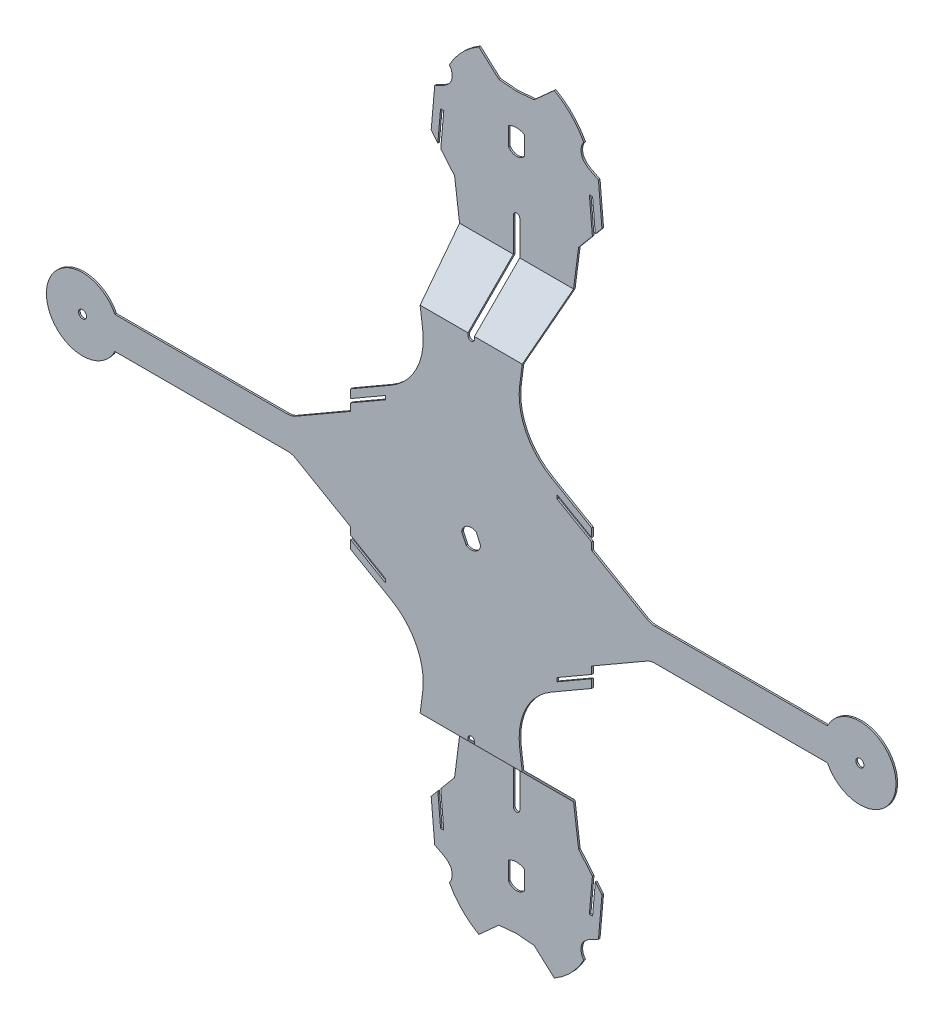
SolidWorks part; units mm, degrees
ref_plane "Alzado" through (0, 0, 0) normal (0, 0, 1) x (1, 0, 0)
ref_plane "Planta" through (0, 0, 0) normal (0, 1, 0) x (1, 0, 0)
ref_plane "Vista lateral" through (0, 0, 0) normal (1, 0, 0) x (0, 0, -1)
sketch "Croquis1" plane through (0, 0, 0) normal (1, 0, 0) x (0, 0, -1)
  line L2 (-31.6304, 0) -> (31.6304, 0) construction
  line L13 (17.5, 0) -> (17.5, 110)
  line L14 (17.5, 110) -> (45.7489, 138.2489)
  line L15 (45.7489, 138.2489) -> (45.7489, 248)
  line L16 (18.5, 0) -> (18.5, 109.5858)
  line L17 (18.5, 109.5858) -> (46.7489, 137.8347)
  line L18 (46.7489, 137.8347) -> (46.7489, 248)
  line L19 (45.7489, 248) -> (46.7489, 248)
  line L20 (45.7489, -248) -> (46.7489, -248)
  line L21 (46.7489, -137.8347) -> (46.7489, -248)
  line L22 (18.5, -109.5858) -> (46.7489, -137.8347)
  line L23 (18.5, 0) -> (18.5, -109.5858)
  line L24 (45.7489, -138.2489) -> (45.7489, -248)
  line L25 (17.5, -110) -> (45.7489, -138.2489)
  line L26 (17.5, 0) -> (17.5, -110)
  point P3 (0, 0)
  dimension "D1" = 17.5
  dimension "D2" = 110
  dimension "D3" = 45
  dimension "D4" = 39.95
  dimension "D5" = 496
  dimension "D6" = 1
extrude "Saliente-Extruir1" add sketch "Croquis1" along normal mid plane 542
sketch "Croquis5" plane through (0, 0, 0) normal (0, 0, 1) x (1, 0, 0)
  line L0 (-923.9507, 561.734) -> (-241.388, 573.6482) construction
sketch "Croquis2" plane through (0, 0, 0) normal (0, 0, 1) x (1, 0, 0)
  line L1 (0, 277.0309) -> (0, -277.0309) construction
  line L9 (-300.4496, 0) -> (300.4496, 0) construction
  line L10 (0, 108.5) -> (0, 159.5) construction
  line L11 (-2, 108.5) -> (-2, 159.5)
  line L12 (2, 108.5) -> (2, 159.5)
  line L13 (-30, 152) -> (-47.205, 172.5041) construction
  line L14 (-53.1684, 179.6111) -> (-50.9701, 204.7381)
  line L15 (-23.5, 239.2795) -> (-11, 228.0419)
  line L34 (-11, 228.0419) -> (0, 227.0795)
  line L35 (-49.0231, 174.6708) -> (-47.3316, 194.0041)
  line L36 (-47.3316, 194.0041) -> (-45.324, 194.0041)
  line L37 (-45.324, 194.0041) -> (-47.205, 172.5041)
  line L38 (-49.0231, 174.6708) -> (-53.1684, 179.6111)
  line L45 (-38.6025, 162.2521) -> (-26.75, 71.1584)
  line L79 (0, 86.6025) -> (-75, 43.3013) construction
  line L83 (-75, 43.3013) -> (-75, 38.0358)
  line L84 (-75, -43.3013) -> (0, -86.6025) construction
  line L85 (0, -86.6025) -> (75, -43.3013) construction
  line L86 (75, -43.3013) -> (75, 43.3013) construction
  line L87 (75, 43.3013) -> (0, 86.6025) construction
  line L88 (-38.6025, 162.2521) -> (-47.205, 172.5041)
  line L89 (-75, 38.0358) -> (-53.5, 50.4489)
  line L90 (-53.5, 50.4489) -> (-53.5, 48.1395)
  line L91 (-53.5, 48.1395) -> (-75, 35.7264)
  line L92 (-221.8444, 10) -> (-111.6613, 10)
  line L93 (-221.8444, -10) -> (-75, -10) construction
  line L94 (-75, 31.1664) -> (-111.6613, 10)
  line L95 (-75, 35.7264) -> (-75, -43.3013) construction
  line L96 (-75, 43.3013) -> (-26.75, 71.1584)
  line L97 (-75, 31.1664) -> (-75, 35.7264)
  line L98 (-221.8444, -10) -> (-111.6613, -10)
  line L99 (-75, -31.1664) -> (-111.6613, -10)
  line L100 (-75, -31.1664) -> (-75, -35.7264)
  line L101 (-53.5, -50.4489) -> (-53.5, -48.1395)
  line L102 (-53.5, -48.1395) -> (-75, -35.7264)
  line L103 (-75, -43.3013) -> (-75, -38.0358)
  line L104 (-75, -38.0358) -> (-53.5, -50.4489)
  line L105 (-75, -43.3013) -> (-26.75, -71.1584)
  line L106 (-38.6025, -162.2521) -> (-26.75, -71.1584)
  line L107 (-38.6025, -162.2521) -> (-47.205, -172.5041)
  line L108 (-45.324, -194.0041) -> (-47.205, -172.5041)
  line L109 (-47.3316, -194.0041) -> (-45.324, -194.0041)
  line L110 (-49.0231, -174.6708) -> (-47.3316, -194.0041)
  line L111 (-49.0231, -174.6708) -> (-53.1684, -179.6111)
  line L112 (-53.1684, -179.6111) -> (-50.9701, -204.7381)
  line L113 (-23.5, -239.2795) -> (-11, -228.0419)
  line L114 (-11, -228.0419) -> (0, -227.0795)
  line L115 (30, 152) -> (47.205, 172.5041) construction
  line L116 (11, -228.0419) -> (0, -227.0795)
  line L117 (23.5, -239.2795) -> (11, -228.0419)
  line L118 (53.1684, -179.6111) -> (50.9701, -204.7381)
  line L119 (49.0231, -174.6708) -> (53.1684, -179.6111)
  line L120 (49.0231, -174.6708) -> (47.3316, -194.0041)
  line L121 (47.3316, -194.0041) -> (45.324, -194.0041)
  line L122 (45.324, -194.0041) -> (47.205, -172.5041)
  line L123 (38.6025, -162.2521) -> (47.205, -172.5041)
  line L124 (38.6025, -162.2521) -> (26.75, -71.1584)
  line L125 (75, -43.3013) -> (26.75, -71.1584)
  line L126 (75, -38.0358) -> (53.5, -50.4489)
  line L127 (75, -43.3013) -> (75, -38.0358)
  line L128 (53.5, -48.1395) -> (75, -35.7264)
  line L129 (53.5, -50.4489) -> (53.5, -48.1395)
  line L130 (75, -31.1664) -> (75, -35.7264)
  line L131 (75, -31.1664) -> (111.6613, -10)
  line L132 (221.8444, -10) -> (111.6613, -10)
  line L133 (75, 31.1664) -> (75, 35.7264)
  line L134 (75, 43.3013) -> (26.75, 71.1584)
  line L135 (75, 31.1664) -> (111.6613, 10)
  line L136 (221.8444, 10) -> (111.6613, 10)
  line L137 (53.5, 48.1395) -> (75, 35.7264)
  line L138 (53.5, 50.4489) -> (53.5, 48.1395)
  line L139 (75, 38.0358) -> (53.5, 50.4489)
  line L140 (38.6025, 162.2521) -> (47.205, 172.5041)
  line L141 (75, 43.3013) -> (75, 38.0358)
  line L142 (38.6025, 162.2521) -> (26.75, 71.1584)
  line L143 (49.0231, 174.6708) -> (53.1684, 179.6111)
  line L144 (45.324, 194.0041) -> (47.205, 172.5041)
  line L145 (47.3316, 194.0041) -> (45.324, 194.0041)
  line L146 (49.0231, 174.6708) -> (47.3316, 194.0041)
  line L147 (11, 228.0419) -> (0, 227.0795)
  line L148 (23.5, 239.2795) -> (11, 228.0419)
  line L149 (53.1684, 179.6111) -> (50.9701, 204.7381)
  line L150 (0, -108.5) -> (0, -159.5) construction
  line L151 (-2, -108.5) -> (-2, -159.5)
  line L152 (2, -108.5) -> (2, -159.5)
  line L154 (-300.4496, 277.0309) -> (300.4496, 277.0309)
  line L155 (-300.4496, 277.0309) -> (-300.4496, -277.0309)
  line L156 (-300.4496, -277.0309) -> (300.4496, -277.0309)
  line L157 (300.4496, 277.0309) -> (300.4496, -277.0309)
  line L158 (-300.4496, 277.0309) -> (300.4496, -277.0309) construction
  line L159 (-300.4496, -277.0309) -> (300.4496, 277.0309) construction
  circle A9 centre (0, 0) radius 247.5 construction
  arc A12 (-2, 108.5) -> (2, 108.5) centre (0, 108.5) ccw
  arc A13 (2, 159.5) -> (-2, 159.5) centre (0, 159.5) ccw
  arc A14 (-41.8968, 220.3811) -> (-23.5, 239.2795) centre (0, 198) cw
  circle A15 centre (0, 198) radius 47.5 construction
  circle A16 centre (0, 0) radius 75 construction
  arc A22 (-221.8444, 10) -> (-221.8444, -10) centre (-242, 0) ccw
  arc A23 (-41.8968, -220.3811) -> (-23.5, -239.2795) centre (0, -198) ccw
  arc A24 (41.8968, -220.3811) -> (23.5, -239.2795) centre (0, -198) cw
  arc A25 (221.8444, 10) -> (221.8444, -10) centre (242, 0) cw
  arc A26 (41.8968, 220.3811) -> (23.5, 239.2795) centre (0, 198) ccw
  arc A27 (-2, -108.5) -> (2, -108.5) centre (0, -108.5) cw
  arc A28 (2, -159.5) -> (-2, -159.5) centre (0, -159.5) cw
  spline S0 degree 3 poles (-50.9701, 204.7381) (-47.793, 206.2687) (-40.7871, 209.0246) (-39.8831, 216.4184) (-40.7368, 219.1761) (-41.8968, 220.3811) knots 0 0 0 0 0.610721 0.773573 1 1 1 1
  spline S1 degree 3 poles (-50.9701, -204.7381) (-47.793, -206.2687) (-40.7871, -209.0246) (-39.8831, -216.4184) (-40.7368, -219.1761) (-41.8968, -220.3811) knots 0 0 0 0 0.610721 0.773573 1 1 1 1
  spline S2 degree 3 poles (50.9701, -204.7381) (47.793, -206.2687) (40.7871, -209.0246) (39.8831, -216.4184) (40.7368, -219.1761) (41.8968, -220.3811) knots 0 0 0 0 0.610721 0.773573 1 1 1 1
  spline S3 degree 3 poles (50.9701, 204.7381) (47.793, 206.2687) (40.7871, 209.0246) (39.8831, 216.4184) (40.7368, 219.1761) (41.8968, 220.3811) knots 0 0 0 0 0.610721 0.773573 1 1 1 1
  point P6 (0, 0)
  point P7 (0, 0)
  point P15 (0, 134)
  point P58 (-53.5, 49.2942)
  point P126 (0, -134)
  dimension "D1" = 495
  dimension "D3" = 242
  dimension "D9" = 198
  dimension "D4" = 150
  dimension "D6" = 45
  dimension "D10" = 134
  dimension "D14" = 152
  dimension "D5" = 95
  dimension "D23" = 21.6
  dimension "D24" = 4.56
  dimension "D7" = 51
  dimension "D8" = 4
  dimension "D11" = 30
  dimension "D12" = 2
  dimension "D13" = 50
  dimension "D15" = 25.1271
  dimension "D16" = 5
  dimension "D17" = 179.6111
  dimension "D18" = 5
  dimension "D19" = 11
  dimension "D20" = 23.5
  dimension "D21" = 12.2
  dimension "D22" = 21.5
  dimension "D25" = 2
  dimension "D26" = 20
  dimension "D27" = 4.56
  dimension "D28" = 53.5
  dimension "D29" = 21.5
sketch "Croquis4" plane through (0, 0, 0) normal (0, 0, 1) x (1, 0, 0)
  line L0 (-326.6263, 0) -> (326.6263, 0) construction
  line L1 (0, 278.5393) -> (0, -278.5393) construction
  line L2 (-5, -194.6834) -> (5, -201.3166) construction
  line L3 (-5, 201.3166) -> (5, 201.3166) construction
  line L4 (-5, 201.3166) -> (-5, 194.6834)
  line L5 (-5, 194.6834) -> (5, 194.6834) construction
  line L6 (5, 201.3166) -> (5, 194.6834)
  line L7 (-5, 201.3166) -> (5, 194.6834) construction
  line L8 (-5, 194.6834) -> (5, 201.3166) construction
  line L9 (-5, -201.3166) -> (5, -194.6834) construction
  line L10 (-5, -194.6834) -> (5, -194.6834) construction
  line L11 (-5, -201.3166) -> (5, -201.3166) construction
  line L12 (5, -201.3166) -> (5, -194.6834)
  line L13 (-5, -201.3166) -> (-5, -194.6834)
  line L20 (-5, 201.3166) -> (-5, 206.0777)
  line L21 (5, 201.3166) -> (5, 206.0777)
  line L26 (-5.9332, 0.8928) -> (3.1299, 5.119) construction
  line L27 (-5.9332, 0.8928) -> (-3.1299, -5.119)
  line L28 (3.1299, 5.119) -> (5.9332, -0.8928)
  line L29 (-3.1299, -5.119) -> (5.9332, -0.8928) construction
  line L30 (0, 0) -> (-1.4017, 3.0059) construction
  line L31 (-8.5, 202.2426) -> (-8.5, 193.7574) construction
  line L32 (8.5, 202.2426) -> (8.5, 193.7574) construction
  line L33 (-5, -194.6834) -> (-5, -189.9223)
  line L34 (5, -194.6834) -> (5, -189.9223)
  line L38 (-8.5, -202.2426) -> (-8.5, -193.7574) construction
  line L39 (8.5, -202.2426) -> (8.5, -193.7574) construction
  arc A0 (-5, 194.6834) -> (5, 194.6834) centre (0, 198) ccw
  arc A1 (-3.1299, -5.119) -> (5.9332, -0.8928) centre (0, 0) ccw
  arc A4 (5, 201.3166) -> (-5, 201.3166) centre (0, 198) ccw construction
  arc A5 (5, -201.3166) -> (-5, -201.3166) centre (0, -198) cw
  arc A6 (-5, -194.6834) -> (5, -194.6834) centre (0, -198) cw construction
  circle A7 centre (-242, 0) radius 2.5
  arc A10 (3.1299, 5.119) -> (-5.9332, 0.8928) centre (0, 0) ccw
  circle A11 centre (242, 0) radius 2.5
  arc A12 (5, 206.0777) -> (-5, 206.0777) centre (0, 198) ccw
  arc A14 (8.5, 202.2426) -> (-8.5, 202.2426) centre (0, 198) ccw construction
  arc A15 (-8.5, 193.7574) -> (8.5, 193.7574) centre (0, 198) ccw construction
  arc A16 (-5, -189.9223) -> (5, -189.9223) centre (0, -198) cw
  arc A18 (-8.5, -193.7574) -> (8.5, -193.7574) centre (0, -198) cw construction
  arc A19 (8.5, -202.2426) -> (-8.5, -202.2426) centre (0, -198) cw construction
  point P4 (0, 0)
  point P8 (0, 0)
  dimension "D3" = 242
  dimension "D4" = 10
  dimension "D5" = 12
  dimension "D6" = 12
  dimension "D2" = 5
  dimension "D1" = 198
  dimension "D7" = 3.5
  dimension "D8" = 10
  dimension "D9" = 25
  dimension "D10" = 3.5
extrude "Cortar-Extruir9" cut sketch "Croquis4" against normal through all both and the other way through all
extrude "Cortar-Extruir10" cut sketch "Croquis2" against normal through all both and the other way through all contours L157 L154 L155 L156 S3 L149 L143 L146 L145 L144 L140 L142 L134 L141 L139 L138 L137 L133 L135 L136 A25 L132 L131 L130 L128 L129 L126 L127 L125 L124 L123 L122 L121 L120 L119 L118 S2 A24 L117 L116 L114 L113 A23 S1 L112 L111 L110 L109 L108 L107 | A28 L152 A27 L151 | L12 A13 L11 A12
fillet "Redondeo1" radius 40 4 edges at (26.75, -71.1584, -18) (-26.75, -71.1584, -18) (-26.75, 71.1584, -18) (26.75, 71.1584, -18)
fillet "Redondeo2" radius 10 4 edges at (-111.6613, -10, -18) (-111.6613, 10, -18) (111.6613, -10, -18) (111.6613, 10, -18)
